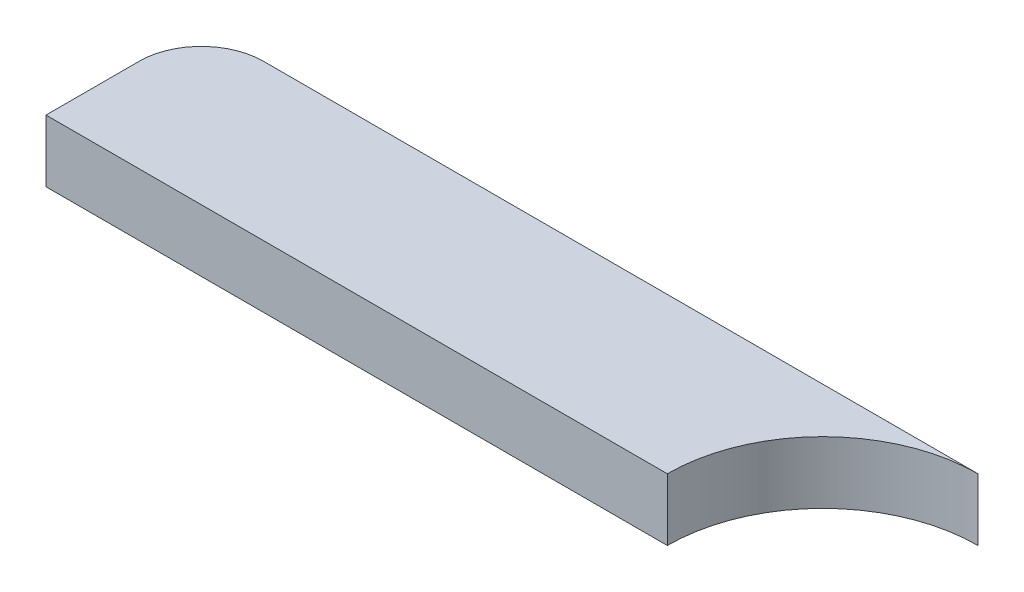
SolidWorks part; units mm, degrees
ref_plane "Front Plane" through (0, 0, 0) normal (0, 0, 1) x (1, 0, 0)
ref_plane "Top Plane" through (0, 0, 0) normal (0, 1, 0) x (1, 0, 0)
ref_plane "Right Plane" through (0, 0, 0) normal (1, 0, 0) x (0, 0, -1)
sketch "Sketch1" plane through (0, 0, 0) normal (0, 1, 0) x (1, 0, 0)
  line L1 (-25, 5) -> (0, 5)
  line L2 (-25, 5) -> (-25, 0)
  line L3 (-25, 0) -> (0, 0)
  line L4 (0, 5) -> (0, 0)
  line L5 (-25, 5) -> (0, 0) construction
  line L6 (-25, 0) -> (0, 5) construction
  circle A0 centre (0, 0) radius 5
  point P0 (0, 0)
  point P2 (0, 0)
  point P3 (-12.5, 2.5)
  point P6 (0, 0)
  dimension "D1" = 10
  dimension "D2" = 25
extrude "Boss-Extrude1" add sketch "Sketch1" along normal blind 2 contours A0 L1 L2 L3
fillet "Fillet1" radius 2 1 edges at (-25, 1, -5)
